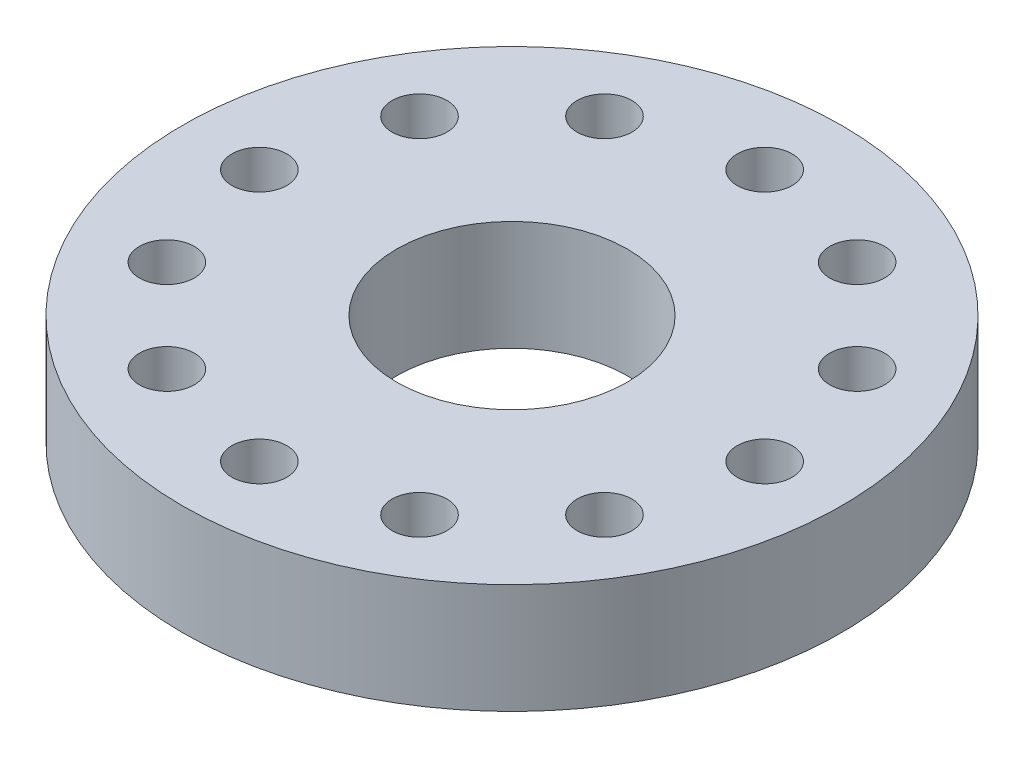
SolidWorks part; units mm, degrees
ref_plane "Front Plane" through (0, 0, 0) normal (0, 0, 1) x (1, 0, 0)
ref_plane "Top Plane" through (0, 0, 0) normal (0, 1, 0) x (1, 0, 0)
ref_plane "Right Plane" through (0, 0, 0) normal (1, 0, 0) x (0, 0, -1)
sketch "Sketch1" plane through (0, 0, 0) normal (0, 1, 0) x (1, 0, 0)
  circle A0 centre (0, 0) radius 30
  circle A1 centre (0, 0) radius 23 construction
  circle A2 centre (0, 23) radius 2.5
  circle A3 centre (11.5, 19.9186) radius 2.5
  circle A4 centre (19.9186, 11.5) radius 2.5
  circle A5 centre (23, 0) radius 2.5
  circle A6 centre (19.9186, -11.5) radius 2.5
  circle A7 centre (11.5, -19.9186) radius 2.5
  circle A8 centre (0, 0) radius 10.5
  circle A9 centre (0, -23) radius 2.5
  circle A10 centre (-11.5, -19.9186) radius 2.5
  circle A11 centre (-19.9186, -11.5) radius 2.5
  circle A12 centre (-23, 0) radius 2.5
  circle A13 centre (-19.9186, 11.5) radius 2.5
  circle A14 centre (-11.5, 19.9186) radius 2.5
  point P18 (0, 0)
  dimension "D1" = 46
  dimension "D2" = 5
  dimension "D4" = 60
  dimension "D5" = 21
  dimension "D3" = 12
extrude "Boss-Extrude1" add sketch "Sketch1" along normal blind 10
